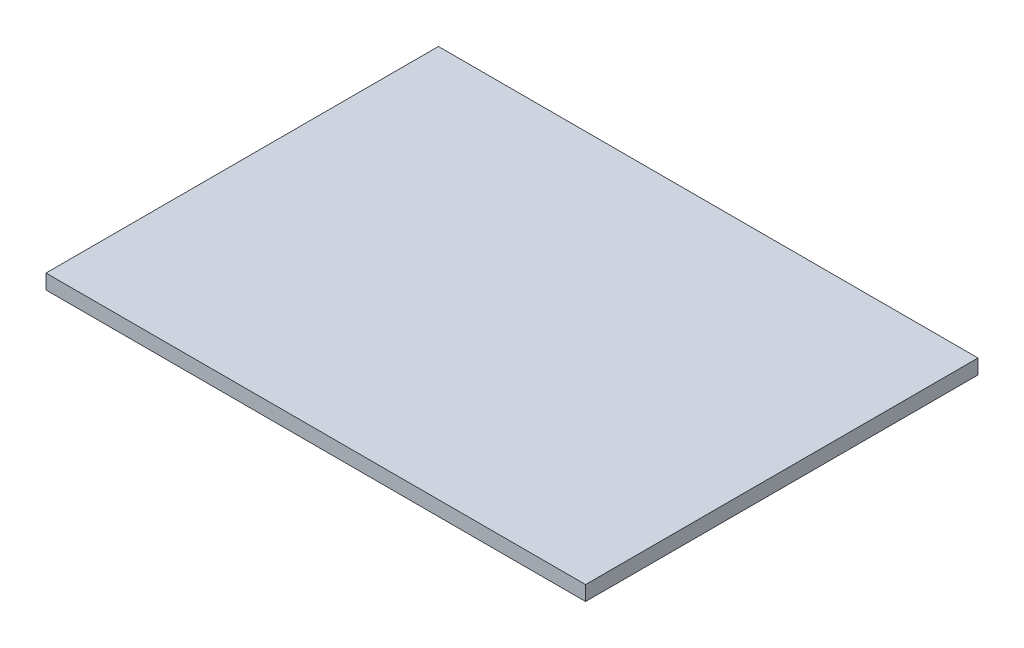
SolidWorks part; units mm, degrees
ref_plane "Front Plane" through (0, 0, 0) normal (0, 0, 1) x (1, 0, 0)
ref_plane "Top Plane" through (0, 0, 0) normal (0, 1, 0) x (1, 0, 0)
ref_plane "Right Plane" through (0, 0, 0) normal (1, 0, 0) x (0, 0, -1)
sketch "Sketch1" plane through (0, 0, 0) normal (0, 1, 0) x (1, 0, 0)
  line L0 (0, 40) -> (-3, 40)
  line L1 (0, 0) -> (52, 0)
  line L3 (0, 40) -> (52, 40)
  line L4 (52, 0) -> (52, 40)
  line L5 (-3, 40) -> (-3, 0)
  line L6 (-3, 0) -> (0, 0)
  dimension "D1" = 52
  dimension "D2" = 40
  dimension "D3" = 3
extrude "Boss-Extrude1" add sketch "Sketch1" along normal blind 1.5
